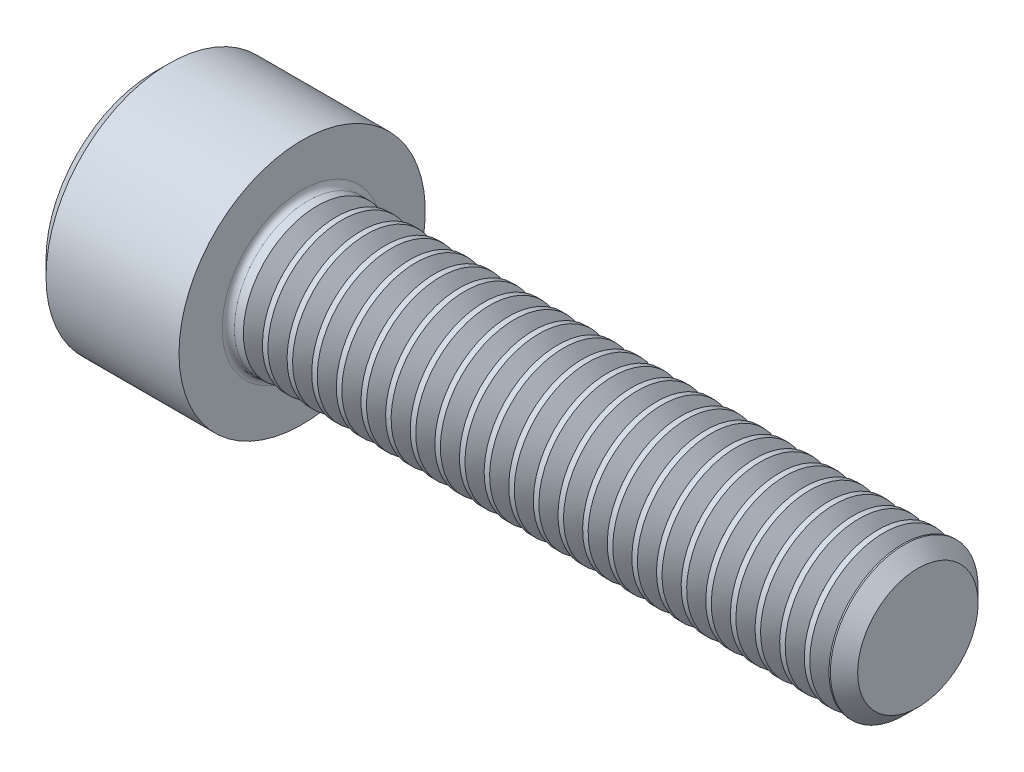
SolidWorks part; units mm, degrees
revolve "Base-Revolve" add sketch "BodySke"
sketch "BodySke" plane through (0, 0, 0) normal (0, 0, 1) x (1, 0, 0)
  line L0 (0, 0) -> (0, 4.4)
  line L1 (0.6, 5) -> (6, 5)
  line L2 (6, 5) -> (6, 3)
  line L3 (6, 3) -> (30.4455, 3)
  line L4 (31, 2.4455) -> (31, 0)
  line L5 (31, 0) -> (0, 0)
  line L6 (-31.75, 0) -> (127, 0) construction
  line L7 (0, 4.4) -> (0.6, 5)
  line L8 (31, 2.4455) -> (30.4455, 3)
  line L9 (0, -4.4) -> (0.6, -5) construction
  line L10 (31, -2.4455) -> (30.4455, -3) construction
  line L11 (7, 9.525) -> (7, 3.175) construction
  line L12 (6, 9.525) -> (6, 3.175) construction
  line L13 (-19, 9.525) -> (-19, 3.175) construction
  dimension "Diameter" = 6
  dimension "Head_ht" = 6
  dimension "Length" = 25
  dimension "Body_ch_ang" = 45
  dimension "Head_dia" = 10
  dimension "Head_ch_ang" = 45
  dimension "Minor_dia" = 4.891
  dimension "Advance" = 1
  dimension "Thread_nom" = 25
  dimension "Thread_length" = 50
  dimension "Head_ch_ht" = 0.6
cosmetic thread "ThreadCosmetic" [suppressed]
fillet "Fillet1" radius 0.25 1 edges at (6, 0, 3)
ref_plane "Plane1" through (0, 0, 0) normal (0, 0, 1) x (1, 0, 0)
ref_plane "Plane2" through (0, 0, 0) normal (0, 1, 0) x (1, 0, 0)
ref_plane "Plane3" through (0, 0, 0) normal (1, 0, 0) x (0, 0, -1)
sketch "Sketch2" plane through (0, 0, 0) normal (0, 0, 1) x (1, 0, 0)
  line L0 (0, 2.542) -> (3, 2.542)
  line L1 (3, 2.542) -> (4.4676, 0)
  line L2 (-31.75, 0) -> (127, 0) construction
  line L3 (4.4676, 0) -> (0, 0)
  line L4 (0, 0) -> (0, 2.542)
  line L5 (0, 4.4) -> (0, -4.4) construction
  line L6 (0, 0) -> (47.625, 0) construction
  line L7 (6, -5) -> (6, 5) construction
  dimension "D1" = 2.542
  dimension "D2" = 60
revolve "Hex-PreBroach" cut sketch "Sketch2" angle 360 about L6
sketch "Sketch3" plane through (0, 0, 0) normal (-1, 0, 0) x (0, 0.5, 0.866)
  line L0 (1.4676, 2.542) -> (-1.4676, 2.542)
  line L1 (-1.4676, 2.542) -> (-2.9352, 0)
  line L2 (1.4676, 2.542) -> (2.9352, 0)
  line L3 (1.4676, -2.542) -> (2.9352, 0)
  line L4 (1.4676, -2.542) -> (-1.4676, -2.542)
  line L5 (-1.4676, -2.542) -> (-2.9352, 0)
  dimension "D1" = 2.542
  dimension "D2" = 2.542
  dimension "Hex_size" = 5.084
extrude "Hex" cut sketch "Sketch3" against normal blind 3
sketch "Sketch4" plane through (0, 0, 0) normal (-1, 0, 0) x (0, 0, 1)
  line L0 (0, 0) -> (2.8067, 0)
  line L1 (0, 0) -> (6.1484, 3.5498) construction
  line L2 (0, 0) -> (1.4033, 2.4307)
  line L3 (2.3336, 0.614) -> (2.6851, 0.817)
  line L4 (1.6986, 1.7139) -> (2.0501, 1.9169)
  arc A0 (2.3336, 0.614) -> (1.6986, 1.7139) centre (0, 0) ccw
  arc A1 (2.8067, 0) -> (2.6851, 0.817) centre (0, 0) ccw
  arc A2 (1.4033, 2.4307) -> (2.0501, 1.9169) centre (0, 0) cw
  dimension "D1" = 30
  dimension "D2" = 60
  dimension "Spline_p_dim" = 1.27
  dimension "D3" = 0.635
extrude "Spline" [suppressed] cut sketch "Sketch4" against normal blind 3
pattern_circular "CirPattern1" [suppressed] count 6 every 60
sketch "Sketch5" plane through (0, 0, 0) normal (0, 0, 1) x (1, 0, 0)
  line L0 (-31.75, 0) -> (127, 0) construction
  line L2 (0, 4.4) -> (0, -4.4) construction
  circle A0 centre (2.3, 0) radius 0.675
  dimension "Drilled_hole_dia" = 1.35
  dimension "Drilled_hole_loc" = 2.3
extrude "Hole" [suppressed] cut sketch "Sketch5" against normal through all and the other way through all
pattern_circular "Drilled-4" [suppressed] count 2 every 60
pattern_circular "Drilled-6" [suppressed] count 3 every 60
sketch "ThdSchSke" plane through (0, 0, 0) normal (0, 0, 1) x (1, 0, 0)
  line L0 (7, -2.4455) -> (6.6117, -3)
  line L1 (7, -2.4455) -> (7.3883, -3)
  line L2 (7.3883, -3) -> (7.3883, -3.75)
  line L3 (-3.175, 0) -> (5.1513, 0) construction
  line L5 (7.3883, -3.75) -> (6.6117, -3.75)
  line L6 (6.6117, -3.75) -> (6.6117, -3)
  line L7 (0, 4.4) -> (0, -4.4) construction
  dimension "Thread_minor" = 4.891
  dimension "Diameter" = 6
  dimension "Start" = 7
revolve "ThreadSchematic" cut sketch "ThdSchSke" angle 360 about L3
pattern_linear "ThdSchPat" count 24 spacing 1 along (1, 0, 0) of "ThreadSchematic"
equation "\"D2@Sketch3\" = \"Hex_size@Sketch3\" / 2"
equation "\"D1@Sketch3\" = \"Hex_size@Sketch3\" / 2"
equation "\"D1@Sketch2\" = \"Hex_size@Sketch3\" / 2"
equation "\"D3@Sketch4\" = \"Spline_p_dim@Sketch4\" / 2"
equation "\"Thread_minor@ThreadCosmetic\"  =  \"Minor_dia@BodySke\""
equation "\"D2@CirPattern1\" = 360 / \"Num_teeth@CirPattern1\""
equation "\"Wall_thickness@Sketch2\" = \"Head_ht@BodySke\" - \"Key_eng@Hex\""
equation "\"Thread_length@ThreadCosmetic\" = ((sgn( (\"Length@BodySke\" - \"Advance@BodySke\" ) - \"Thread_nom@BodySke\" )-1)*( (\"Length@BodySke\" - \"Advance@BodySke\" ) - \"Thread_nom@BodySke\" ))/-2+ \"Thread_nom@BodySke\""
equation "\"Thread_minor@ThdSchSke\" = \"Minor_dia@BodySke\""
equation "\"Diameter@ThdSchSke\" = \"Diameter@BodySke\""
equation "\"Overcut@ThdSchSke\" = \"Diameter@BodySke\" * 1.25"
equation "\"Start@ThdSchSke\" = \"Head_ht@BodySke\" + \"Length@BodySke\" - \"Thread_length@ThreadCosmetic\"  '---Non-countersunk---"
equation "\"Num_threads@ThdSchPat\" = int( \"Thread_length@ThreadCosmetic\" / \"Advance@BodySke\" + 0.999 )  + 1"
equation "\"Advance@ThdSchPat\" = \"Thread_length@ThreadCosmetic\" /  (\"Num_threads@ThdSchPat\" - 1) 'relax it"
equation "\"Num_threads@ThdSchPat\" = \"Num_threads@ThdSchPat\" - sgn( \"Num_threads@ThdSchPat\" - 1) '---chamfered tips only---"
